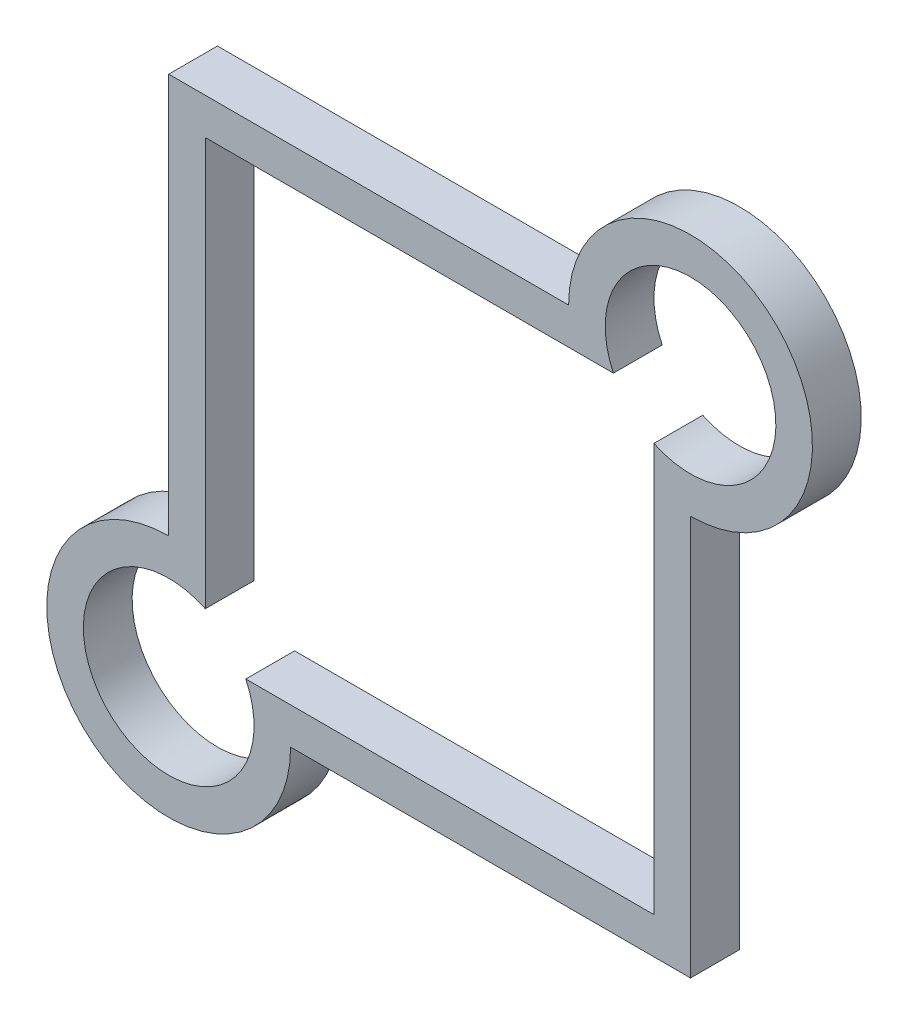
SolidWorks part; units mm, degrees
ref_plane "Front Plane" through (0, 0, 0) normal (0, 0, 1) x (1, 0, 0)
ref_plane "Top Plane" through (0, 0, 0) normal (0, 1, 0) x (1, 0, 0)
ref_plane "Right Plane" through (0, 0, 0) normal (1, 0, 0) x (0, 0, -1)
sketch "Sketch4" plane through (0, 0, 0) normal (0, 0, 1) x (1, 0, 0)
  line L1 (0, 214) -> (164, 214)
  line L2 (0, 214) -> (0, 50)
  line L3 (50, 0) -> (214, 0)
  line L4 (214, 164) -> (214, 0)
  line L5 (31.6228, 15) -> (199, 15)
  line L6 (15, 31.6228) -> (15, 199)
  line L7 (15, 199) -> (182.3772, 199)
  line L8 (199, 15) -> (199, 182.3772)
  arc A0 (214, 164) -> (164, 214) centre (214, 214) ccw
  arc A1 (199, 182.3772) -> (182.3772, 199) centre (214, 214) ccw
  arc A2 (0, 50) -> (50, 0) centre (0, 0) ccw
  arc A3 (15, 31.6228) -> (31.6228, 15) centre (0, 0) ccw
  dimension "D3" = 15
  dimension "D1" = 214
  dimension "D2" = 214
  dimension "D4" = 15
  dimension "D5" = 15
  dimension "D6" = 15
extrude "Boss-Extrude1" add sketch "Sketch4" along normal blind 20
